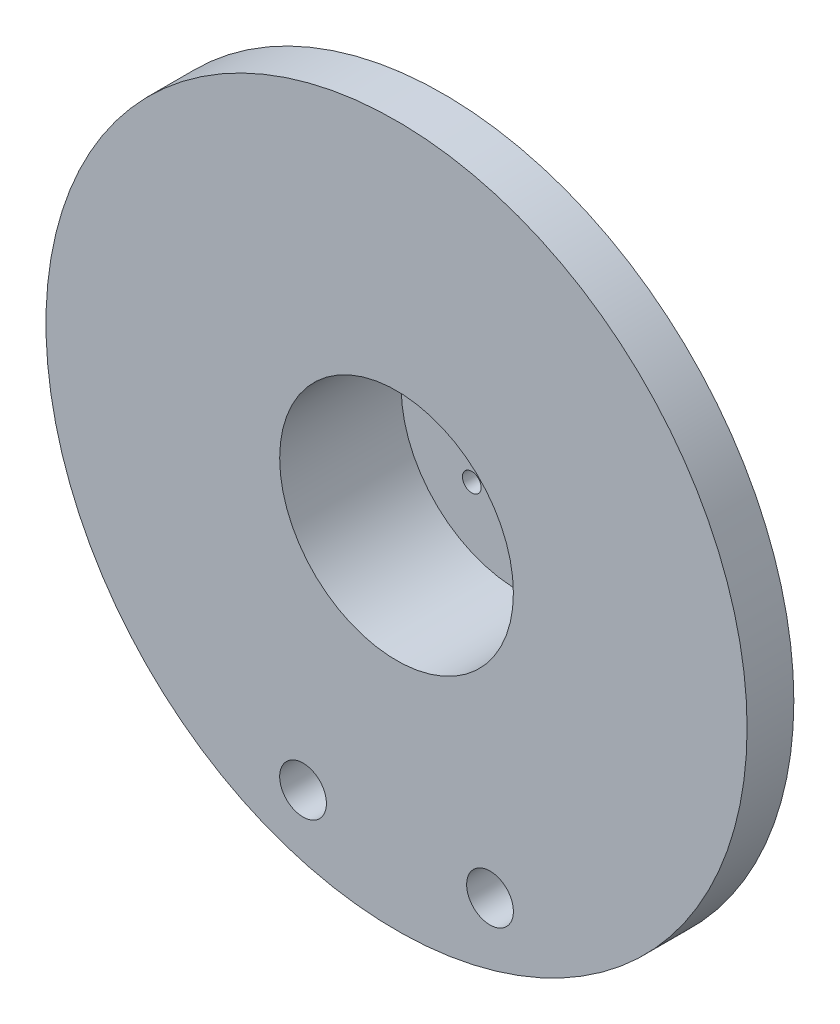
SolidWorks part; units mm, degrees
ref_plane "前视基准面" through (0, 0, 0) normal (0, 0, 1) x (1, 0, 0)
ref_plane "上视基准面" through (0, 0, 0) normal (0, 1, 0) x (1, 0, 0)
ref_plane "右视基准面" through (0, 0, 0) normal (1, 0, 0) x (0, 0, -1)
sketch "草图1" plane through (0, 0, 0) normal (0, 0, 1) x (1, 0, 0)
  circle A0 centre (0, 0) radius 37.5
  circle A1 centre (0, 0) radius 12.5
  dimension "D1" = 75
  dimension "D2" = 25
extrude "凸台-拉伸1" add sketch "草图1" along normal blind 5
sketch "草图2" plane through (0, 0, 0) normal (0, 0, -1) x (-1, 0, 0)
  circle A0 centre (0, 0) radius 12.5
  circle A1 centre (0, 0) radius 17.5
  dimension "D1" = 25
  dimension "D2" = 35
extrude "凸台-拉伸2" add sketch "草图2" along normal blind 13
sketch "草图3" plane through (0, 0, -13) normal (0, 0, -1) x (-1, 0, 0)
  circle A0 centre (0, 0) radius 12.5
  circle A1 centre (0, 0) radius 5
  circle A2 centre (7, 0) radius 1
  circle A3 centre (4.9497, -4.9497) radius 1
  circle A4 centre (0, -7) radius 1
  circle A5 centre (-4.9497, -4.9497) radius 1
  circle A6 centre (-7, 0) radius 1
  circle A7 centre (-4.9497, 4.9497) radius 1
  circle A8 centre (0, 7) radius 1
  circle A9 centre (4.9497, 4.9497) radius 1
  point P22 (0, 0)
  dimension "D1" = 10
  dimension "D2" = 7
  dimension "D3" = 2
  dimension "D4" = 8
extrude "凸台-拉伸3" add sketch "草图3" against normal blind 5
sketch "草图4" plane through (0, 0, 5) normal (0, 0, 1) x (1, 0, 0)
  line L0 (-10, -29.5) -> (10, -29.5) construction
  line L1 (-23, -25.5) -> (23, -25.5) construction
  line L2 (-23, -25.5) -> (-23, 25.5) construction
  line L3 (-23, 25.5) -> (23, 25.5) construction
  line L4 (23, -25.5) -> (23, 25.5) construction
  line L5 (-23, -25.5) -> (23, 25.5) construction
  line L6 (-23, 25.5) -> (23, -25.5) construction
  line L7 (-16.8523, -25.5) -> (16.8523, -25.5) construction
  line L8 (-16.8523, -25.5) -> (-16.8523, -33.5) construction
  line L9 (-16.8523, -33.5) -> (16.8523, -33.5) construction
  line L10 (16.8523, -25.5) -> (16.8523, -33.5) construction
  circle A0 centre (0, 0) radius 37.5 construction
  circle A1 centre (10, -29.5) radius 2.5
  circle A2 centre (-10, -29.5) radius 2.5
  point P0 (0, 0)
  point P16 (0, -29.5)
  dimension "D4" = 5
  dimension "D5" = 5
  dimension "D1" = 46
  dimension "D2" = 51
  dimension "D3" = 8
  dimension "D6" = 20
extrude "切除-拉伸1" cut sketch "草图4" against normal blind 5
